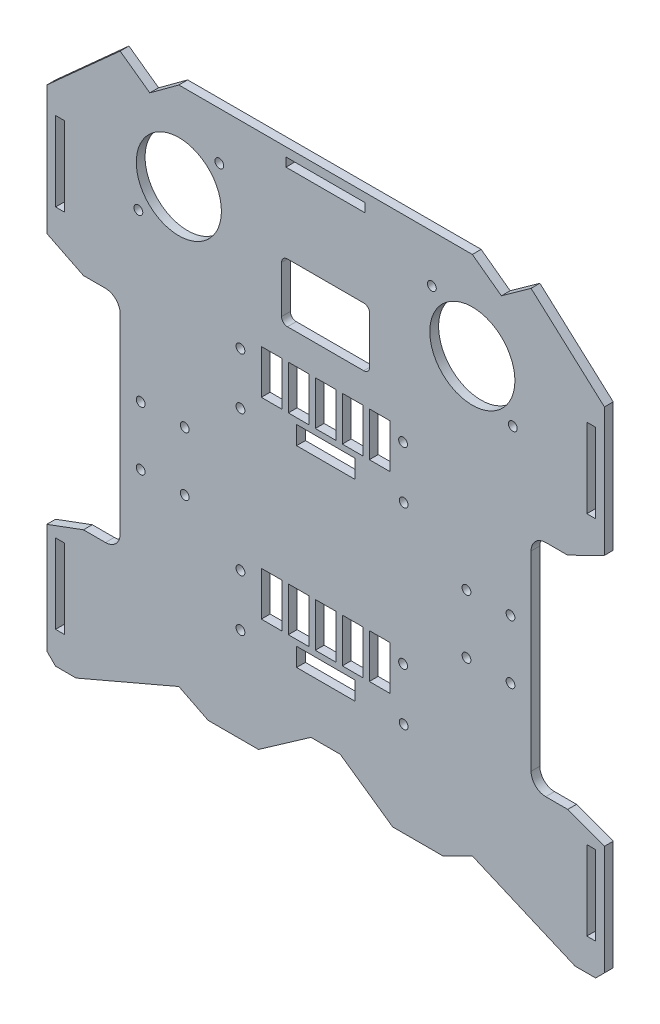
SolidWorks part; units mm, degrees
ref_plane "Front Plane" through (0, 0, 0) normal (0, 0, 1) x (1, 0, 0)
ref_plane "Top Plane" through (0, 0, 0) normal (0, 1, 0) x (1, 0, 0)
ref_plane "Right Plane" through (0, 0, 0) normal (1, 0, 0) x (0, 0, -1)
sketch "Model" plane through (0, 0, 0) normal (0, 0, 1) x (1, 0, 0)
  line L0 (190, 103.6976) -> (190, 147.5)
  line L1 (25, 92.5) -> (25, 27.5)
  line L2 (20, 22.5) -> (12.5, 22.5)
  line L3 (177.5, 97.5) -> (170, 97.5)
  line L4 (165, 92.5) -> (165, 27.5)
  line L5 (170, 22.5) -> (177.5, 22.5)
  line L6 (45, 170) -> (145, 170)
  line L7 (0, 0) -> (0, -19.5)
  line L8 (190, 0) -> (190, -19.5)
  line L9 (0, 147.5) -> (25, 170)
  line L10 (25, 170) -> (35.1079, 162.725)
  line L11 (35.1079, 162.725) -> (45, 170)
  line L12 (190, 147.5) -> (165, 170)
  line L13 (165, 170) -> (154.8921, 162.725)
  line L14 (154.8921, 162.725) -> (145, 170)
  line L15 (0, 147.5) -> (0, 103.6976)
  line L17 (0, 17.8675) -> (0, 0)
  line L18 (190, 17.8675) -> (190, 0)
  line L19 (90, 0) -> (100, 0)
  line L20 (0, 17.8675) -> (12.5, 22.5)
  line L21 (0, 103.6976) -> (12.5, 97.5)
  line L22 (190, 17.8675) -> (177.5, 22.5)
  line L23 (190, 103.6976) -> (177.5, 97.5)
  line L24 (12.5, 97.5) -> (20, 97.5)
  line L25 (3, -22.5) -> (10, -22.5)
  line L26 (10, -22.5) -> (45, -7.5)
  line L27 (45, -7.5) -> (55, -12.5)
  line L28 (72.1429, -12.5) -> (90, 0)
  line L29 (55, -12.5) -> (72.1429, -12.5)
  line L30 (100, 0) -> (117.8571, -12.5)
  line L31 (135, -12.5) -> (145, -7.5)
  line L32 (145, -7.5) -> (180, -22.5)
  line L33 (180, -22.5) -> (187, -22.5)
  line L34 (117.8571, -12.5) -> (135, -12.5)
  line L35 (0, -19.5) -> (3, -22.5)
  line L36 (187, -22.5) -> (190, -19.5)
  line L37 (3, 140) -> (6, 140)
  line L38 (6, 140) -> (6, 113)
  line L39 (6, 113) -> (3, 113)
  line L40 (3, 113) -> (3, 140)
  line L41 (187, 140) -> (184, 140)
  line L42 (184, 140) -> (184, 113)
  line L43 (184, 113) -> (187, 113)
  line L44 (187, 113) -> (187, 140)
  line L45 (81.5, 167) -> (108.5, 167)
  line L46 (108.5, 167) -> (108.5, 164)
  line L47 (108.5, 164) -> (81.5, 164)
  line L48 (81.5, 164) -> (81.5, 167)
  line L49 (73.1, 106.8909) -> (80.1, 106.8909)
  line L50 (80.1, 106.8909) -> (80.1, 91.8909)
  line L51 (80.1, 91.8909) -> (73.1, 91.8909)
  line L52 (73.1, 91.8909) -> (73.1, 106.8909)
  line L53 (82.3, 106.8909) -> (89.3, 106.8909)
  line L54 (89.3, 106.8909) -> (89.3, 91.8909)
  line L55 (89.3, 91.8909) -> (82.3, 91.8909)
  line L56 (82.3, 91.8909) -> (82.3, 106.8909)
  line L57 (91.5, 106.8909) -> (98.5, 106.8909)
  line L58 (98.5, 106.8909) -> (98.5, 91.8909)
  line L59 (98.5, 91.8909) -> (91.5, 91.8909)
  line L60 (91.5, 91.8909) -> (91.5, 106.8909)
  line L61 (100.7, 106.8909) -> (107.7, 106.8909)
  line L62 (107.7, 106.8909) -> (107.7, 91.8909)
  line L63 (107.7, 91.8909) -> (100.7, 91.8909)
  line L64 (100.7, 91.8909) -> (100.7, 106.8909)
  line L65 (109.9, 106.8909) -> (116.9, 106.8909)
  line L66 (116.9, 106.8909) -> (116.9, 91.8909)
  line L67 (116.9, 91.8909) -> (109.9, 91.8909)
  line L68 (109.9, 91.8909) -> (109.9, 106.8909)
  line L69 (85.121, 89.882) -> (105.096, 89.882)
  line L70 (105.096, 89.882) -> (105.096, 83.632)
  line L71 (105.096, 83.632) -> (85.121, 83.632)
  line L72 (85.121, 83.632) -> (85.121, 89.882)
  line L73 (73.1, 41.4457) -> (80.1, 41.4457)
  line L74 (80.1, 41.4457) -> (80.1, 26.4457)
  line L75 (80.1, 26.4457) -> (73.1, 26.4457)
  line L76 (73.1, 26.4457) -> (73.1, 41.4457)
  line L77 (82.3, 41.4457) -> (89.3, 41.4457)
  line L78 (89.3, 41.4457) -> (89.3, 26.4457)
  line L79 (89.3, 26.4457) -> (82.3, 26.4457)
  line L80 (82.3, 26.4457) -> (82.3, 41.4457)
  line L81 (91.5, 41.4457) -> (98.5, 41.4457)
  line L82 (98.5, 41.4457) -> (98.5, 26.4457)
  line L83 (98.5, 26.4457) -> (91.5, 26.4457)
  line L84 (91.5, 26.4457) -> (91.5, 41.4457)
  line L85 (100.7, 41.4457) -> (107.7, 41.4457)
  line L86 (107.7, 41.4457) -> (107.7, 26.4457)
  line L87 (107.7, 26.4457) -> (100.7, 26.4457)
  line L88 (100.7, 26.4457) -> (100.7, 41.4457)
  line L89 (109.9, 41.4457) -> (116.9, 41.4457)
  line L90 (116.9, 41.4457) -> (116.9, 26.4457)
  line L91 (116.9, 26.4457) -> (109.9, 26.4457)
  line L92 (109.9, 26.4457) -> (109.9, 41.4457)
  line L93 (85.121, 24.4368) -> (105.096, 24.4368)
  line L94 (105.096, 24.4368) -> (105.096, 18.1868)
  line L95 (105.096, 18.1868) -> (85.121, 18.1868)
  line L96 (85.121, 18.1868) -> (85.121, 24.4368)
  line L97 (80, 119.1728) -> (80, 135.1728)
  line L98 (110, 119.1728) -> (110, 135.1728)
  line L99 (82, 117.1728) -> (108, 117.1728)
  line L100 (82, 137.1728) -> (108, 137.1728)
  line L101 (3, 15.375) -> (6, 15.375)
  line L102 (6, 15.375) -> (6, -11.625)
  line L103 (6, -11.625) -> (3, -11.625)
  line L104 (3, -11.625) -> (3, 15.375)
  line L105 (184, 15.375) -> (187, 15.375)
  line L106 (187, 15.375) -> (187, -11.625)
  line L107 (187, -11.625) -> (184, -11.625)
  line L108 (184, -11.625) -> (184, 15.375)
  circle A0 centre (32, 50) radius 1.5
  circle A1 centre (47, 50) radius 1.5
  circle A2 centre (32, 70) radius 1.5
  circle A3 centre (47, 70) radius 1.5
  circle A4 centre (158, 70) radius 1.5
  circle A5 centre (143, 70) radius 1.5
  circle A6 centre (158, 50) radius 1.5
  circle A7 centre (143, 50) radius 1.5
  circle A8 centre (45, 140) radius 14.5
  circle A9 centre (31.2114, 126.2114) radius 1.5
  circle A10 centre (58.7886, 153.7886) radius 1.5
  circle A11 centre (145, 140) radius 14.5
  circle A12 centre (158.7886, 126.2114) radius 1.5
  circle A13 centre (131.2114, 153.7886) radius 1.5
  arc A14 (25, 92.5) -> (20, 97.5) centre (20, 92.5) ccw
  arc A15 (20, 22.5) -> (25, 27.5) centre (20, 27.5) ccw
  arc A16 (170, 97.5) -> (165, 92.5) centre (170, 92.5) ccw
  arc A17 (165, 27.5) -> (170, 22.5) centre (170, 27.5) ccw
  circle A18 centre (65.996, 37.2868) radius 1.5
  circle A19 centre (65.996, 19.6618) radius 1.5
  circle A20 centre (121.396, 37.3868) radius 1.5
  circle A21 centre (121.596, 19.6618) radius 1.5
  circle A22 centre (65.996, 85.107) radius 1.5
  circle A23 centre (65.996, 102.732) radius 1.5
  circle A24 centre (121.396, 102.832) radius 1.5
  circle A25 centre (121.596, 85.107) radius 1.5
  arc A26 (82, 137.1728) -> (80, 135.1728) centre (82, 135.1728) ccw
  arc A27 (80, 119.1728) -> (82, 117.1728) centre (82, 119.1728) ccw
  arc A28 (110, 135.1728) -> (108, 137.1728) centre (108, 135.1728) ccw
  arc A29 (108, 117.1728) -> (110, 119.1728) centre (108, 119.1728) ccw
extrude "Boss-Extrude1" add sketch "Model" along normal blind 3
